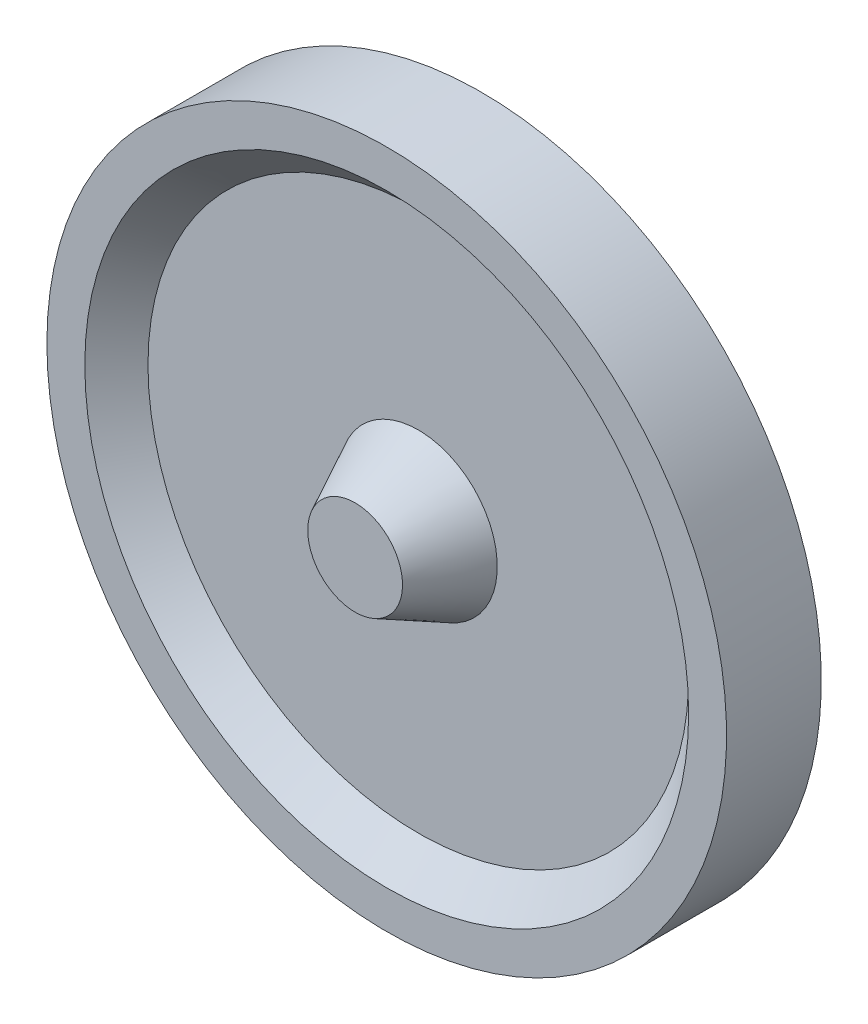
SolidWorks part; units mm, degrees
ref_plane "Front Plane" through (0, 0, 0) normal (0, 0, 1) x (1, 0, 0)
ref_plane "Top Plane" through (0, 0, 0) normal (0, 1, 0) x (1, 0, 0)
ref_plane "Right Plane" through (0, 0, 0) normal (1, 0, 0) x (0, 0, -1)
sketch "Sketch3" plane through (0, 0, 0) normal (0, 1, 0) x (1, 0, 0)
  line L0 (17.1198, 1) -> (19.1198, 3)
  line L4 (21.5211, 3) -> (21.5211, -3)
  line L5 (17.1198, -1) -> (19.1198, -3)
  line L6 (19.1198, 3) -> (21.5211, 3)
  line L15 (0, 5) -> (3, 5)
  line L17 (0, -5) -> (3, -5)
  line L19 (0, 9.9928) -> (0, -9.9037) construction
  line L20 (0, 5) -> (0, -5)
  line L21 (3, 5) -> (5, 1)
  line L22 (19.1198, -3) -> (21.5211, -3)
  line L23 (3, -5) -> (5, -1)
  line L27 (5, 1) -> (17.1198, 1)
  line L28 (5, -1) -> (17.1198, -1)
  point P0 (0, 0)
  point P6 (0, 0)
  point P12 (0, 0)
  point P14 (0, 0)
  dimension "D1" = 6
  dimension "D4" = 2
  dimension "D5" = 2
  dimension "D6" = 2
  dimension "D8" = 10
  dimension "D9" = 2
  dimension "D12" = 2
revolve "Revolve1" add sketch "Sketch3" angle 360 about L19
